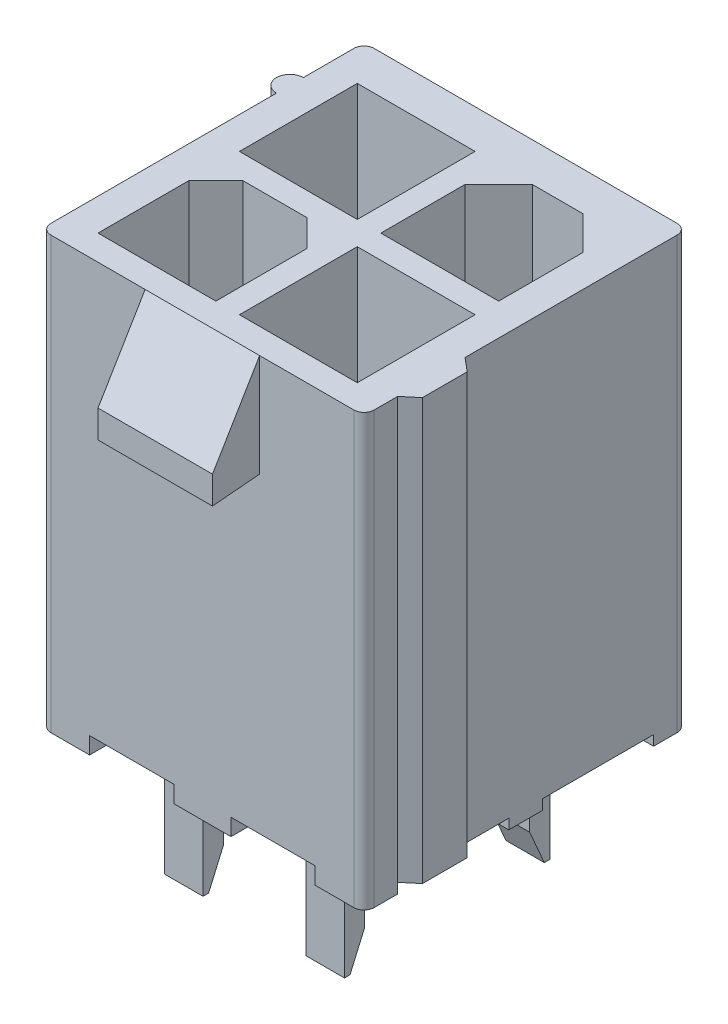
SolidWorks part; units mm, degrees
ref_plane "Front Plane" through (0, 0, 0) normal (0, 0, 1) x (1, 0, 0)
ref_plane "Top Plane" through (0, 0, 0) normal (0, 1, 0) x (1, 0, 0)
ref_plane "Right Plane" through (0, 0, 0) normal (1, 0, 0) x (0, 0, -1)
ref_plane "Plane1" through (0, 0.3, 0) normal (0, -1, 0) x (1, 0, 0)
sketch "Sketch1" plane through (0, 0.3, 0) normal (0, -1, 0) x (1, 0, 0)
  line L0 (-4.8, -4.8) -> (1.7, -4.8)
  line L1 (1.7, -4.8) -> (1.7, 4.8)
  line L2 (1.7, 4.8) -> (-4.8, 4.8)
  line L3 (-4.8, 4.8) -> (-4.8, -2.2)
  line L4 (-4.8, -3) -> (-4.8, -4.8)
  arc A0 (-4.8, -2.2) -> (-4.8, -3) centre (-4.8, -2.6) ccw
extrude "Boss-Extrude1" add sketch "Sketch1" against normal blind 12.5
ref_plane "Plane2" through (1.7, 0, 0) normal (1, 0, 0) x (0, 0, -1)
sketch "Sketch2" plane through (1.7, 0, 0) normal (1, 0, 0) x (0, 0, -1)
  line L0 (-4.8, 12.8) -> (-6.2, 10.45)
  line L1 (-6.2, 10.45) -> (-6.2, 9.6275)
  line L2 (-6.2, 9.6275) -> (-4.8, 9.6275)
  line L3 (-4.8, 9.6275) -> (-4.8, 12.8)
extrude "Boss-Extrude2" add sketch "Sketch2" against normal blind 3.4
sketch "Sketch3" plane through (1.7, 0, 0) normal (1, 0, 0) x (0, 0, -1)
  line L0 (4.8, 0.3) -> (-4.8, 0.3)
  line L1 (-4.8, 0.3) -> (-4.8, 12.8)
  line L2 (-4.8, 12.8) -> (4.8, 12.8)
  line L3 (4.8, 12.8) -> (4.8, 0.3)
extrude "Boss-Extrude3" add sketch "Sketch3" along normal blind 3.5
sketch "Sketch4" plane through (0, 12.8, 0) normal (0, 1, 0) x (-1, 0, 0)
  line L0 (-5.2, -4.8) -> (-4.8, -4.8)
  line L1 (-4.8, -4.8) -> (-4.8, 2.1356)
  line L2 (-4.8, 2.1356) -> (-5.2, 2.1356)
  line L3 (-5.2, 2.1356) -> (-5.2, -4.8)
extrude "Cut-Extrude1" cut sketch "Sketch4" against normal through all
sketch "Sketch5" plane through (0, 0, -4.8) normal (0, 0, -1) x (-1, 0, 0)
  line L0 (-3.35, 0.3) -> (3.35, 0.3)
  line L1 (3.35, 0.3) -> (3.35, 0.5)
  line L2 (3.35, 0.5) -> (-3.35, 0.5)
  line L3 (-3.35, 0.5) -> (-3.35, 0.3)
extrude "Cut-Extrude2" cut sketch "Sketch5" against normal through all
sketch "Sketch6" plane through (0, 0.3, 0) normal (0, -1, 0) x (1, 0, 0)
  line L0 (4.8, -4.8) -> (3.35, -4.8)
  line L1 (3.35, -4.8) -> (3.35, 0.5)
  line L2 (3.35, 0.5) -> (4.8, 0.5)
  line L3 (4.8, 0.5) -> (4.8, -4.8)
extrude "Boss-Extrude4" add sketch "Sketch6" along normal blind 0.3
sketch "Sketch7" plane through (0, 0.5, 0) normal (0, -1, 0) x (1, 0, 0)
  line L0 (0.85, -4.8) -> (-0.85, -4.8)
  line L1 (-0.85, -4.8) -> (-0.85, 4.8)
  line L2 (-0.85, 4.8) -> (0.85, 4.8)
  line L3 (0.85, 4.8) -> (0.85, -4.8)
extrude "Boss-Extrude5" add sketch "Sketch7" along normal blind 0.5
sketch "Sketch8" plane through (0, 0.3, 0) normal (0, -1, 0) x (1, 0, 0)
  line L0 (-4.8, -4.8) -> (-4.8, -3.8)
  line L1 (-4.8, -3.8) -> (-3.35, -3.8)
  line L2 (-3.35, -3.8) -> (-3.35, -4.8)
  line L3 (-3.35, -4.8) -> (-4.8, -4.8)
extrude "Boss-Extrude6" add sketch "Sketch8" along normal blind 0.3
sketch "Sketch9" plane through (0, 0.3, 0) normal (0, -1, 0) x (1, 0, 0)
  line L0 (5.2, 4.8) -> (4.8, 4.8)
  line L1 (4.8, 4.8) -> (4.8, 3.4644)
  line L2 (4.8, 3.4644) -> (5.2, 3.4644)
  line L3 (5.2, 3.4644) -> (5.2, 4.8)
extrude "Cut-Extrude3" cut sketch "Sketch9" against normal through all
sketch "Sketch10" plane through (0, 0.3, 0) normal (0, -1, 0) x (1, 0, 0)
  line L0 (4.8, 4.8) -> (4.8, 3.8)
  line L1 (4.8, 3.8) -> (3.35, 3.8)
  line L2 (3.35, 3.8) -> (3.35, 4.8)
  line L3 (3.35, 4.8) -> (4.8, 4.8)
extrude "Boss-Extrude7" add sketch "Sketch10" along normal blind 0.3
sketch "Sketch11" plane through (0, 0.3, 0) normal (0, -1, 0) x (1, 0, 0)
  line L0 (-4.8, 4.8) -> (-3.35, 4.8)
  line L1 (-3.35, 4.8) -> (-3.35, -0.5)
  line L2 (-3.35, -0.5) -> (-4.8, -0.5)
  line L3 (-4.8, -0.5) -> (-4.8, 4.8)
extrude "Boss-Extrude8" add sketch "Sketch11" along normal blind 0.3
sketch "Sketch12" plane through (0, 0.3, 0) normal (0, -1, 0) x (1, 0, 0)
  line L0 (-4.8, -2.2) -> (-4.8, -3)
  arc A0 (-4.8, -3) -> (-4.8, -2.2) centre (-4.8, -2.6) cw
extrude "Boss-Extrude9" add sketch "Sketch12" along normal blind 0.3
sketch "Sketch13" plane through (-0.85, 0, 0) normal (-1, 0, 0) x (0, 0, 1)
  line L0 (0.5, 0) -> (3.8, 0)
  line L1 (3.8, 0) -> (3.8, 0.3)
  line L2 (3.8, 0.3) -> (0.5, 0.3)
  line L3 (0.5, 0.3) -> (0.5, 0)
extrude "Cut-Extrude4" cut sketch "Sketch13" against normal through all
sketch "Sketch14" plane through (-0.85, 0, 0) normal (-1, 0, 0) x (0, 0, 1)
  line L0 (-3.8, 0) -> (-0.5, 0)
  line L1 (-0.5, 0) -> (-0.5, 0.3)
  line L2 (-0.5, 0.3) -> (-3.8, 0.3)
  line L3 (-3.8, 0.3) -> (-3.8, 0)
extrude "Cut-Extrude5" cut sketch "Sketch14" against normal blind 1.7
sketch "Sketch15" plane through (-4.8, 0, 0) normal (-1, 0, 0) x (0, 0, 1)
  line L0 (0.5, 0) -> (3.8, 0)
  line L1 (3.8, 0) -> (3.8, 0.3)
  line L2 (3.8, 0.3) -> (0.5, 0.3)
  line L3 (0.5, 0.3) -> (0.5, 0)
extrude "Cut-Extrude6" cut sketch "Sketch15" against normal through all
sketch "Sketch16" plane through (4.8, 0, 0) normal (1, 0, 0) x (0, 0, -1)
  line L0 (0.5, 0) -> (3.8, 0)
  line L1 (3.8, 0) -> (3.8, 0.3)
  line L2 (3.8, 0.3) -> (0.5, 0.3)
  line L3 (0.5, 0.3) -> (0.5, 0)
extrude "Cut-Extrude7" cut sketch "Sketch16" against normal up to next
ref_plane "Plane3" through (1.53, 0, 0) normal (-1, 0, 0) x (0, -1, 0)
sketch "Sketch17" plane through (1.53, 0, 0) normal (-1, 0, 0) x (0, -1, 0)
  line L0 (2.5, 2.65) -> (3.5, 3.085)
  line L1 (3.5, 3.085) -> (3.5, 3.25)
  line L2 (3.5, 3.25) -> (-0.5, 3.25)
  line L3 (-0.5, 3.25) -> (-0.5, 2.65)
  line L4 (-0.5, 2.65) -> (2.5, 2.65)
extrude "Boss-Extrude10" add sketch "Sketch17" against normal blind 1.14
sketch "Sketch18" plane through (1.53, 0, 0) normal (-1, 0, 0) x (0, -1, 0)
  line L0 (3.5, -2.85) -> (3.5, -2.685)
  line L1 (3.5, -2.685) -> (2.5, -2.25)
  line L2 (2.5, -2.25) -> (-0.5, -2.25)
  line L3 (-0.5, -2.25) -> (-0.5, -2.85)
  line L4 (-0.5, -2.85) -> (3.5, -2.85)
extrude "Boss-Extrude11" add sketch "Sketch18" against normal blind 1.14
ref_plane "Plane4" through (-2.67, 0, 0) normal (-1, 0, 0) x (0, -1, 0)
sketch "Sketch19" plane through (-2.67, 0, 0) normal (-1, 0, 0) x (0, -1, 0)
  line L0 (2.5, 2.65) -> (3.5, 3.085)
  line L1 (3.5, 3.085) -> (3.5, 3.25)
  line L2 (3.5, 3.25) -> (-0.5, 3.25)
  line L3 (-0.5, 3.25) -> (-0.5, 2.65)
  line L4 (-0.5, 2.65) -> (2.5, 2.65)
extrude "Boss-Extrude12" add sketch "Sketch19" against normal blind 1.14
sketch "Sketch20" plane through (-2.67, 0, 0) normal (-1, 0, 0) x (0, -1, 0)
  line L0 (3.5, -2.85) -> (3.5, -2.685)
  line L1 (3.5, -2.685) -> (2.5, -2.25)
  line L2 (2.5, -2.25) -> (-0.5, -2.25)
  line L3 (-0.5, -2.25) -> (-0.5, -2.85)
  line L4 (-0.5, -2.85) -> (3.5, -2.85)
extrude "Boss-Extrude13" add sketch "Sketch20" against normal blind 1.14
sketch "Sketch21" plane through (0, 12.8, 0) normal (0, 1, 0) x (-1, 0, 0)
  line L0 (0.35, 4.05) -> (0.35, 0.55)
  line L1 (0.35, 0.55) -> (3.85, 0.55)
  line L2 (3.85, 0.55) -> (3.85, 4.05)
  line L3 (3.85, 4.05) -> (0.35, 4.05)
extrude "Cut-Extrude8" cut sketch "Sketch21" against normal blind 9.1
sketch "Sketch22" plane through (0, 3.7, 0) normal (0, 1, 0) x (-1, 0, 0)
  line L0 (1.53, 1.73) -> (1.53, 2.87)
  line L1 (1.53, 2.87) -> (2.67, 2.87)
  line L2 (2.67, 2.87) -> (2.67, 1.73)
  line L3 (2.67, 1.73) -> (1.53, 1.73)
extrude "Boss-Extrude14" add sketch "Sketch22" along normal blind 5.6
sketch "Sketch23" plane through (0, 12.8, 0) normal (0, 1, 0) x (-1, 0, 0)
  line L0 (-3.85, 4.05) -> (-3.85, 0.55)
  line L1 (-3.85, 0.55) -> (-0.35, 0.55)
  line L2 (-0.35, 0.55) -> (-0.35, 4.05)
  line L3 (-0.35, 4.05) -> (-3.85, 4.05)
extrude "Cut-Extrude9" cut sketch "Sketch23" against normal blind 9.1
sketch "Sketch24" plane through (0, 3.7, 0) normal (0, 1, 0) x (-1, 0, 0)
  line L0 (-2.67, 1.73) -> (-2.67, 2.87)
  line L1 (-2.67, 2.87) -> (-1.53, 2.87)
  line L2 (-1.53, 2.87) -> (-1.53, 1.73)
  line L3 (-1.53, 1.73) -> (-2.67, 1.73)
extrude "Boss-Extrude15" add sketch "Sketch24" along normal blind 5.6
sketch "Sketch25" plane through (0, 12.8, 0) normal (0, 1, 0) x (-1, 0, 0)
  line L0 (-3.85, -0.15) -> (-3.85, -3.65)
  line L1 (-3.85, -3.65) -> (-0.35, -3.65)
  line L2 (-0.35, -3.65) -> (-0.35, -0.15)
  line L3 (-0.35, -0.15) -> (-3.85, -0.15)
extrude "Cut-Extrude10" cut sketch "Sketch25" against normal blind 9.1
sketch "Sketch26" plane through (0, 3.7, 0) normal (0, 1, 0) x (-1, 0, 0)
  line L0 (-2.67, -2.47) -> (-2.67, -1.33)
  line L1 (-2.67, -1.33) -> (-1.53, -1.33)
  line L2 (-1.53, -1.33) -> (-1.53, -2.47)
  line L3 (-1.53, -2.47) -> (-2.67, -2.47)
extrude "Boss-Extrude16" add sketch "Sketch26" along normal blind 5.6
sketch "Sketch27" plane through (0, 12.8, 0) normal (0, 1, 0) x (-1, 0, 0)
  line L0 (0.35, -0.15) -> (0.35, -3.65)
  line L1 (0.35, -3.65) -> (3.85, -3.65)
  line L2 (3.85, -3.65) -> (3.85, -0.15)
  line L3 (3.85, -0.15) -> (0.35, -0.15)
extrude "Cut-Extrude11" cut sketch "Sketch27" against normal blind 9.1
sketch "Sketch28" plane through (0, 3.7, 0) normal (0, 1, 0) x (-1, 0, 0)
  line L0 (1.53, -2.47) -> (1.53, -1.33)
  line L1 (1.53, -1.33) -> (2.67, -1.33)
  line L2 (2.67, -1.33) -> (2.67, -2.47)
  line L3 (2.67, -2.47) -> (1.53, -2.47)
extrude "Boss-Extrude17" add sketch "Sketch28" along normal blind 5.6
draft "Draft1" type of draft neutral plane draft angle 5 faces to draft 1 face at (-0.425, 9.6275, 5.675) neutral plane through (-1.7, 10.45, 6.2) neutral plane normal (0, 0, 1) reverse direction yes parameters "D1"=5
draft "Draft2" type of draft neutral plane draft angle 40 faces to draft 2 face at (5, 6.55, 3.4644) face at (5, 6.55, 2.1356) neutral plane through (5.2, 0, 0) neutral plane normal (1, 0, 0) parameters "D1"=40
chamfer "Chamfer1" distance 1 angle 45 2 edges at (3.85, 8.25, -3.65) (0.35, 8.25, -3.65)
chamfer "Chamfer2" distance 0.8 angle 45 2 edges at (-3.85, 8.25, 0.55) (-0.35, 8.25, 0.55)
fillet "Fillet1" radius 0.3 4 edges at (-4.8, 6.4, 4.8) (4.8, 6.4, -4.8) (4.8, 6.4, 4.8) (-4.8, 6.4, -4.8)
sketch "Sketch29" plane through (0, 0, 0) normal (0, -1, 0) x (1, 0, 0)
  line L0 (-3.35, -3.8) -> (3.35, 3.8) construction
  point P4 (0, 0)
ref_plane "Plane5" through (0, 0, 0) normal (0, 0, 1) x (1, 0, 0)
sketch "Sketch30" plane through (0, 0, 0) normal (0, 0, 1) x (1, 0, 0)
  line L0 (0, 0) -> (0, -5.7638) construction
